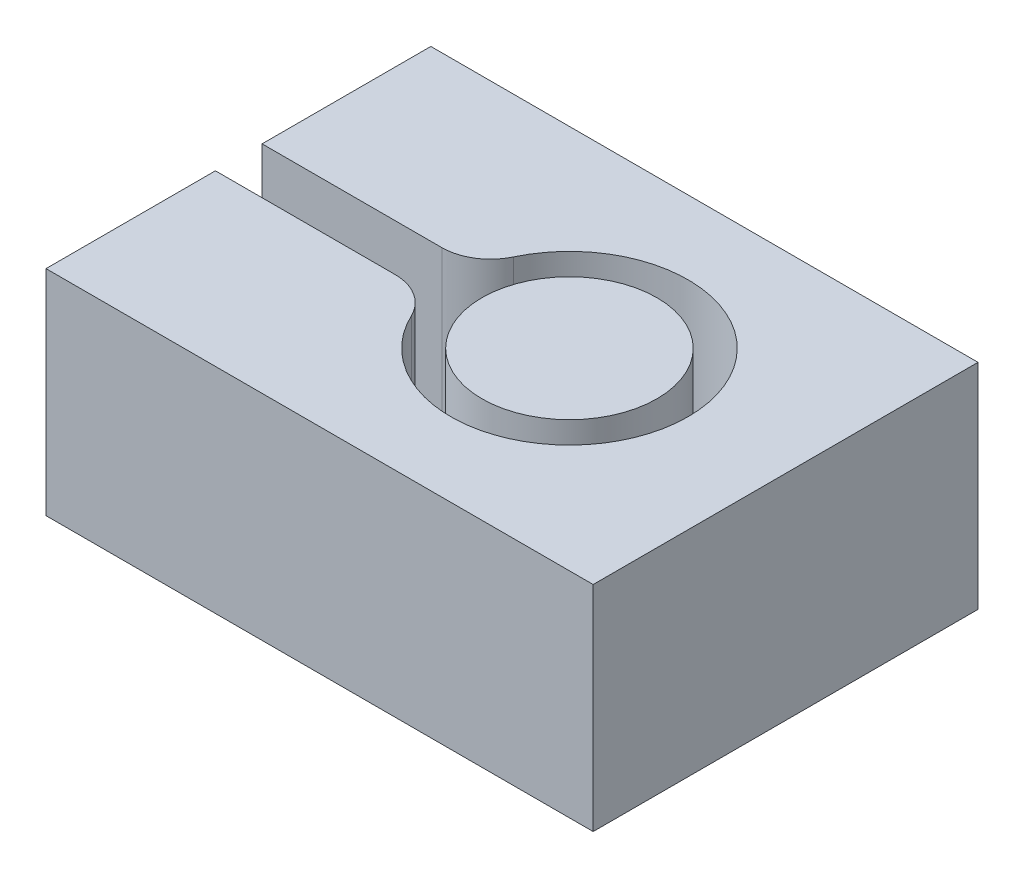
SolidWorks part; units mm, degrees
ref_plane "Front Plane" through (0, 0, 0) normal (0, 0, 1) x (1, 0, 0)
ref_plane "Top Plane" through (0, 0, 0) normal (0, 1, 0) x (1, 0, 0)
ref_plane "Right Plane" through (0, 0, 0) normal (1, 0, 0) x (0, 0, -1)
sketch "Sketch1" plane through (0, 0, 0) normal (0, 1, 0) x (1, 0, 0)
  line L0 (0, 10.6587) -> (0, 0)
  line L1 (0, 0) -> (25.1281, 0)
  line L2 (25.1281, 0) -> (25.1281, 19.783)
  line L3 (25.1281, 19.783) -> (0, 19.783)
  line L4 (0, 19.783) -> (0, 11.4087)
  line L5 (0, 11.4087) -> (5.7193, 11.4087)
  line L6 (5.7193, 11.4087) -> (10.717, 13.7392)
  line L7 (10.717, 13.7392) -> (10.7382, 13.7763)
  line L8 (10.7382, 13.7763) -> (10.7662, 13.8073)
  line L9 (10.7662, 13.8073) -> (10.8, 13.8319)
  line L10 (10.8, 13.8319) -> (10.8382, 13.8489)
  line L11 (10.8382, 13.8489) -> (10.8791, 13.8576)
  line L12 (10.8791, 13.8576) -> (10.9209, 13.8576)
  line L13 (10.9209, 13.8576) -> (10.9618, 13.8489)
  line L14 (10.9618, 13.8489) -> (11, 13.8319)
  line L15 (11, 13.8319) -> (11.0338, 13.8073)
  line L16 (11.0338, 13.8073) -> (11.0506, 13.7887)
  line L17 (11.0506, 13.7887) -> (18.67, 13.7887)
  line L18 (18.67, 13.7887) -> (18.7865, 13.9904)
  line L19 (18.7865, 13.9904) -> (18.9963, 14.2234)
  line L20 (18.9963, 14.2234) -> (19.25, 14.4077)
  line L21 (19.25, 14.4077) -> (19.5365, 14.5353)
  line L22 (19.5365, 14.5353) -> (19.8432, 14.6005)
  line L23 (19.8432, 14.6005) -> (20.1568, 14.6005)
  line L24 (20.1568, 14.6005) -> (20.4635, 14.5353)
  line L25 (20.4635, 14.5353) -> (20.75, 14.4077)
  line L26 (20.75, 14.4077) -> (21.0037, 14.2234)
  line L27 (21.0037, 14.2234) -> (21.2135, 13.9904)
  line L28 (21.2135, 13.9904) -> (21.3703, 13.7188)
  line L29 (21.3703, 13.7188) -> (21.4672, 13.4206)
  line L30 (21.4672, 13.4206) -> (21.5, 13.1087)
  line L31 (21.5, 13.1087) -> (21.5, 2.9087)
  line L32 (21.5, 2.9087) -> (19.5, 2.9087)
  line L33 (19.5, 2.9087) -> (19.5, 11.6984)
  line L34 (19.5, 11.6984) -> (19.25, 11.8097)
  line L35 (19.25, 11.8097) -> (18.9963, 11.994)
  line L36 (18.9963, 11.994) -> (18.7865, 12.227)
  line L37 (18.7865, 12.227) -> (18.7509, 12.2887)
  line L38 (18.7509, 12.2887) -> (18.2, 12.2887)
  line L39 (18.2, 12.2887) -> (18.2, 13.0387)
  line L40 (18.2, 13.0387) -> (17.2, 13.0387)
  line L41 (17.2, 13.0387) -> (17.2, 12.2887)
  line L42 (17.2, 12.2887) -> (16.2, 12.2887)
  line L43 (16.2, 12.2887) -> (16.2, 13.0387)
  line L44 (16.2, 13.0387) -> (15.2, 13.0387)
  line L45 (15.2, 13.0387) -> (15.2, 12.2887)
  line L46 (15.2, 12.2887) -> (14.2, 12.2887)
  line L47 (14.2, 12.2887) -> (14.2, 13.0387)
  line L48 (14.2, 13.0387) -> (13.2, 13.0387)
  line L49 (13.2, 13.0387) -> (13.2, 12.2887)
  line L50 (13.2, 12.2887) -> (12.2, 12.2887)
  line L51 (12.2, 12.2887) -> (12.2, 13.0387)
  line L52 (12.2, 13.0387) -> (11.2362, 13.0387)
  line L53 (11.2362, 13.0387) -> (11.5091, 12.4534)
  line L54 (11.5091, 12.4534) -> (11.2, 12.3093)
  line L55 (11.2, 12.3093) -> (11.1558, 12.2887)
  line L56 (11.1558, 12.2887) -> (10.6028, 12.0308)
  line L57 (10.6028, 12.0308) -> (10.2858, 12.7106)
  line L58 (10.2858, 12.7106) -> (9.3795, 12.2879)
  line L59 (9.3795, 12.2879) -> (9.6965, 11.6082)
  line L60 (9.6965, 11.6082) -> (8.7901, 11.1856)
  line L61 (8.7901, 11.1856) -> (8.4732, 11.8653)
  line L62 (8.4732, 11.8653) -> (7.5669, 11.4427)
  line L63 (7.5669, 11.4427) -> (7.8838, 10.763)
  line L64 (7.8838, 10.763) -> (6.9775, 10.3404)
  line L65 (6.9775, 10.3404) -> (6.6606, 11.0201)
  line L66 (6.6606, 11.0201) -> (6, 10.7121)
  line L67 (6, 10.7121) -> (6, 9.9087)
  line L68 (6, 9.9087) -> (5, 9.9087)
  line L69 (5, 9.9087) -> (5, 10.6587)
  line L70 (5, 10.6587) -> (4, 10.6587)
  line L71 (4, 10.6587) -> (4, 9.9087)
  line L72 (4, 9.9087) -> (3, 9.9087)
  line L73 (3, 9.9087) -> (3, 10.6587)
  line L74 (3, 10.6587) -> (2, 10.6587)
  line L75 (2, 10.6587) -> (2, 9.9087)
  line L76 (2, 9.9087) -> (1, 9.9087)
  line L77 (1, 9.9087) -> (1, 10.6587)
  line L78 (1, 10.6587) -> (0, 10.6587)
sketch "Sketch2" plane through (0, 0, 0) normal (0, 1, 0) x (1, 0, 0)
  line L0 (0, 11.4087) -> (0, 8.4087)
  line L1 (0, 19.783) -> (25.1281, 19.783)
  line L2 (0, 19.783) -> (0, 0)
  line L3 (0, 0) -> (25.1281, 0)
  line L4 (25.1281, 19.783) -> (25.1281, 0)
  line L5 (0, 8.4087) -> (8, 8.4087)
  line L6 (0, 11.4087) -> (8, 11.4087)
  line L8 (12.5, 9.9087) -> (17, 9.9087)
  line L9 (8, 11.4087) -> (9.0905, 11.4087)
  line L10 (8, 8.4087) -> (9.0905, 8.4087)
  circle A0 centre (17, 9.9087) radius 4.5
  arc A1 (11.698, 6.8922) -> (11.698, 12.9252) centre (17, 9.9087) ccw
  circle A2 centre (17, 9.9087) radius 6.1 construction
  arc A3 (11.698, 6.8922) -> (9.0905, 8.4087) centre (9.0905, 5.4087) ccw
  arc A4 (11.698, 12.9252) -> (9.0905, 11.4087) centre (9.0905, 14.4087) cw
  dimension "D1" = 1.6
  dimension "D2" = 3
extrude "Boss-Extrude3" add sketch "Sketch2" along normal blind 8
sketch "Sketch4" plane through (0, 0, 0) normal (0, -1, 0) x (1, 0, 0)
  line L1 (25.1281, -19.783) -> (0, -19.783)
  line L2 (25.1281, -19.783) -> (25.1281, 0)
  line L3 (25.1281, 0) -> (0, 0)
  line L4 (0, -19.783) -> (0, 0)
extrude "Boss-Extrude4" add sketch "Sketch4" along normal blind 3
sketch "Sketch5" plane through (25.1281, 0, 0) normal (1, 0, 0) x (0, 0, -1)
  line L4 (0, 8) -> (0, -3)
  line L5 (0, -3) -> (19.783, -3)
  line L6 (19.783, -3) -> (19.783, 8)
  line L7 (19.783, 8) -> (0, 8)
  line L8 (0, 8) -> (0, -3)
  line L9 (0, -3) -> (19.783, -3)
  line L10 (19.783, -3) -> (19.783, 8)
  line L11 (19.783, 8) -> (0, 8)
  dimension "D1" = 0
extrude "Boss-Extrude5" add sketch "Sketch5" along normal blind 3
sketch "Sketch6" plane through (0, 8, 0) normal (0, 1, 0) x (1, 0, 0)
  line L0 (0, 9.9087) -> (0, 11.1087)
  line L1 (0, 8.4087) -> (0, 11.4087) construction
  line L2 (0, 11.1087) -> (0, 8.7087)
  line L3 (0, 8.7087) -> (9.2366, 8.7087)
  line L4 (0, 11.1087) -> (9.2366, 11.1087)
  line L5 (0, 8.4087) -> (9.0905, 8.4087) construction
  line L6 (0, 11.4087) -> (9.0905, 11.4087) construction
  line L7 (0, 8.4087) -> (9.0905, 8.4087)
  line L8 (0, 11.4087) -> (9.0905, 11.4087)
  line L9 (0, 11.1087) -> (0, 11.4087)
  line L10 (0, 8.7087) -> (0, 8.4087)
  arc A1 (11.698, 12.9252) -> (11.4934, 12.5331) centre (17, 9.9087) ccw
  arc A2 (11.698, 6.8922) -> (9.0905, 8.4087) centre (9.0905, 5.4087) ccw construction
  arc A3 (9.0905, 11.4087) -> (11.698, 12.9252) centre (9.0905, 14.4087) ccw construction
  arc A4 (11.698, 6.8922) -> (9.0905, 8.4087) centre (9.0905, 5.4087) ccw
  arc A5 (9.0905, 11.4087) -> (11.698, 12.9252) centre (9.0905, 14.4087) ccw
  arc A6 (11.4934, 7.2843) -> (11.698, 6.8922) centre (17, 9.9087) ccw
  arc A7 (11.4934, 12.5331) -> (9.2366, 11.1087) centre (9.2366, 13.6087) cw
  arc A8 (11.4934, 7.2843) -> (9.2366, 8.7087) centre (9.2366, 6.2087) ccw
  point P21 (11.0192, 8.7087)
  arc M12 (9.0905, 11.4087) -> (11.698, 12.9252) centre (9.0905, 14.4087) ccw
  arc M14 (11.698, 6.8922) -> (9.0905, 8.4087) centre (9.0905, 5.4087) ccw
  line M15 (9.0905, 8.4087) -> (0, 8.4087)
  line M21 (0, 11.4087) -> (9.0905, 11.4087)
  dimension "D1" = 2.5
  dimension "D2" = 2.5
extrude "Boss-Extrude6" add sketch "Sketch6" against normal up to surface (8 mm away) contours A7 A1 L9 L4 M12 M21 | A6 A8 L3 L10 M15 M14 up to face at (17, 0, -14.4087)
sketch "Sketch7" plane through (0, 8, 0) normal (0, 1, 0) x (1, 0, 0)
  line L0 (0, 19.783) -> (0, 11.1087) construction
  line L1 (0, 11.1087) -> (9.2366, 11.1087) construction
  line L2 (9.2366, 8.7087) -> (0, 8.7087) construction
  line L3 (0, 8.7087) -> (0, 0) construction
  line L4 (0, 0) -> (28.1281, 0) construction
  line L5 (28.1281, 0) -> (28.1281, 19.783) construction
  line L6 (28.1281, 19.783) -> (0, 19.783) construction
  line L7 (0, 19.783) -> (0, 11.1087)
  line L8 (0, 11.1087) -> (9.2366, 11.1087)
  line L9 (9.2366, 8.7087) -> (0, 8.7087)
  line L10 (0, 8.7087) -> (0, 0)
  line L11 (0, 0) -> (28.1281, 0)
  line L12 (28.1281, 0) -> (28.1281, 19.783)
  line L13 (28.1281, 19.783) -> (0, 19.783)
  circle A0 centre (17, 9.9087) radius 4.5 construction
  arc A1 (9.2366, 11.1087) -> (11.4934, 12.5331) centre (9.2366, 13.6087) ccw construction
  arc A2 (11.4934, 7.2843) -> (11.4934, 12.5331) centre (17, 9.9087) ccw construction
  arc A3 (11.4934, 7.2843) -> (9.2366, 8.7087) centre (9.2366, 6.2087) ccw construction
  circle A4 centre (17, 9.9087) radius 4.5
  arc A5 (9.2366, 11.1087) -> (11.4934, 12.5331) centre (9.2366, 13.6087) ccw
  arc A6 (11.4934, 7.2843) -> (11.4934, 12.5331) centre (17, 9.9087) ccw
  arc A7 (11.4934, 7.2843) -> (9.2366, 8.7087) centre (9.2366, 6.2087) ccw
